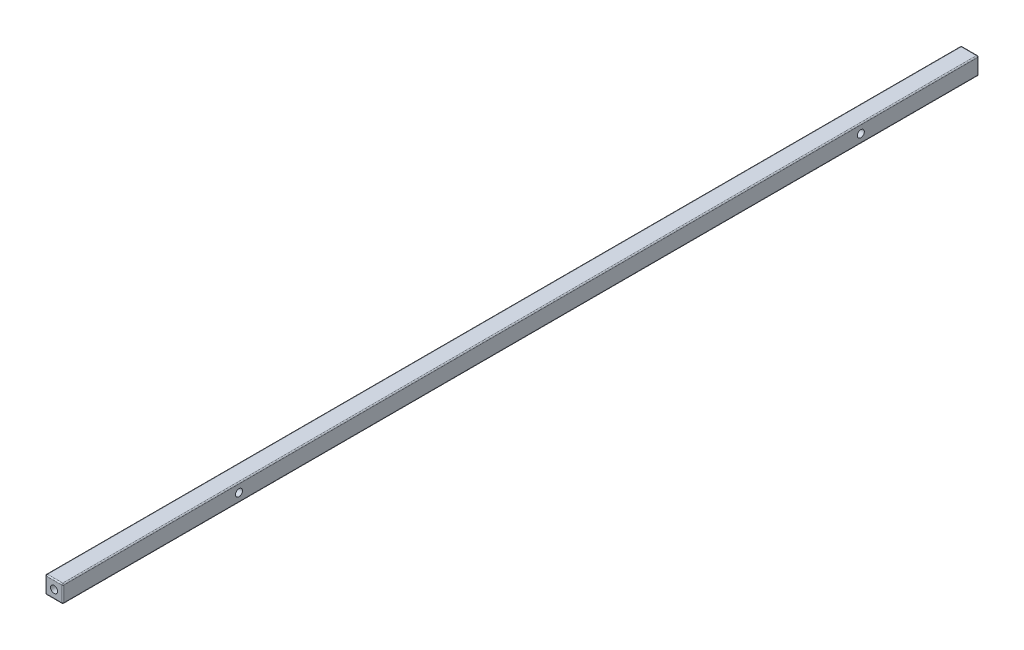
SolidWorks part; units mm, degrees
material "1023 Carbon Steel Sheet (SS)"
ref_plane "Ön Düzlem" through (0, 0, 0) normal (0, 0, 1) x (1, 0, 0)
ref_plane "Üst Düzlem" through (0, 0, 0) normal (0, 1, 0) x (1, 0, 0)
ref_plane "Sağ Düzlem" through (0, 0, 0) normal (1, 0, 0) x (0, 0, -1)
sketch "Sketch1" plane through (0, 0, 0) normal (0, 0, 1) x (1, 0, 0)
  line L0 (0, 0) -> (15, 0)
  line L1 (15, 0) -> (15, 15)
  line L2 (15, 15) -> (0, 15)
  line L3 (0, 15) -> (0, 0)
  dimension "D1" = 15
extrude "Boss-Extrude1" add sketch "Sketch1" along normal blind 785 contours L2 L3 L0 L1
sketch "Sketch2" plane through (0, 0, 0) normal (0, 0, -1) x (-1, 0, 0)
  line L0 (-15, 0) -> (-15, 15) construction
  line L1 (-15, 15) -> (0, 15) construction
  circle A0 centre (-7.5, 7.5) radius 3
  dimension "D1" = 7.5
  dimension "D3" = 6
  dimension "D2" = 7.5
extrude "Cut-Extrude1" cut sketch "Sketch2" against normal blind 5 contours A0
sketch "Sketch3" plane through (0, 0, 785) normal (0, 0, 1) x (1, 0, 0)
  line L0 (0, 15) -> (0, 0) construction
  line L1 (15, 15) -> (0, 15) construction
  circle A0 centre (7.5, 7.5) radius 3
  dimension "D1" = 7.5
  dimension "D2" = 7.5
  dimension "D3" = 6
extrude "Cut-Extrude2" cut sketch "Sketch3" against normal blind 5 contours A0
fillet "Fillet1" radius 1 12 edges at (0, 7.5, 0) (7.5, 0, 0) (15, 7.5, 0) (7.5, 15, 0) (15, 0, 392.5) (15, 15, 392.5) (7.5, 0, 785) (15, 7.5, 785) (7.5, 15, 785) (0, 7.5, 785) (0, 15, 392.5) (0, 0, 392.5)
sketch "Sketch5" plane through (15, 0, 0) normal (1, 0, 0) x (0, 0, -1)
  line L0 (-1, 1) -> (-1, 14) construction
  line L1 (-784, 15) -> (-1, 15) construction
  line L2 (-784, 14) -> (-784, 1) construction
  line L3 (-1, 0) -> (-784, 0) construction
  circle A0 centre (-101, 7.5) radius 3
  circle A1 centre (-634, 7.5) radius 3
  dimension "D1" = 100
  dimension "D2" = 6
  dimension "D4" = 150
  dimension "D6" = 6
  dimension "D3" = 7.5
  dimension "D5" = 7.5
extrude "Cut-Extrude4" cut sketch "Sketch5" against normal through all
